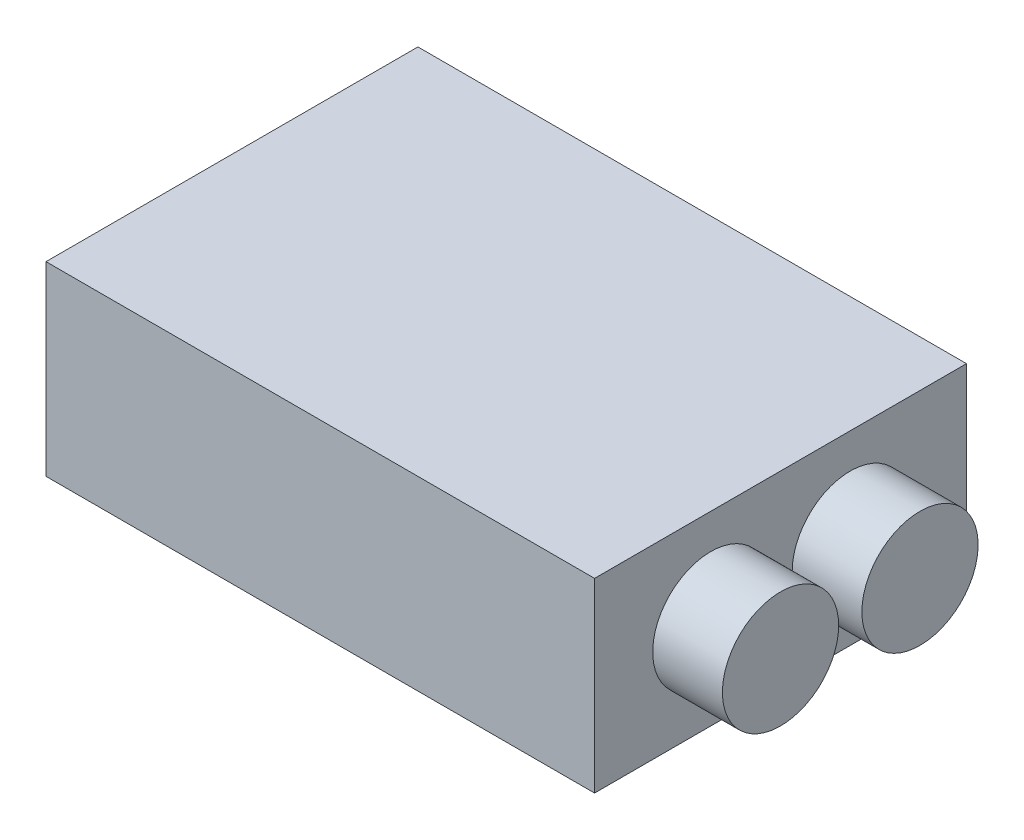
SolidWorks part; units mm, degrees
ref_plane "Front Plane" through (0, 0, 0) normal (0, 0, 1) x (1, 0, 0)
ref_plane "Top Plane" through (0, 0, 0) normal (0, 1, 0) x (1, 0, 0)
ref_plane "Right Plane" through (0, 0, 0) normal (1, 0, 0) x (0, 0, -1)
sketch "Sketch2" plane through (0, 0, 0) normal (0, 1, 0) x (1, 0, 0)
  line L1 (0, 0) -> (118, 0)
  line L2 (0, 0) -> (0, -80)
  line L3 (0, -80) -> (118, -80)
  line L4 (118, 0) -> (118, -80)
  dimension "D1" = 118
  dimension "D2" = 80
extrude "Boss-Extrude1" add sketch "Sketch2" along normal blind 40
sketch "Sketch3" plane through (118, 0, 0) normal (1, 0, 0) x (0, 0, -1)
  line L0 (-40, 45.5259) -> (-40, -9.5868) construction
  line L1 (-80, 40) -> (-80, 0) construction
  line L2 (-80, 0) -> (0, 0) construction
  circle A0 centre (-55, 20) radius 12.5
  circle A1 centre (-25, 20) radius 12.5
  point P10 (0, 0)
  dimension "D1" = 25
  dimension "D2" = 25
  dimension "D3" = 20
  dimension "D4" = 40
extrude "Boss-Extrude2" add sketch "Sketch3" along normal blind 15
